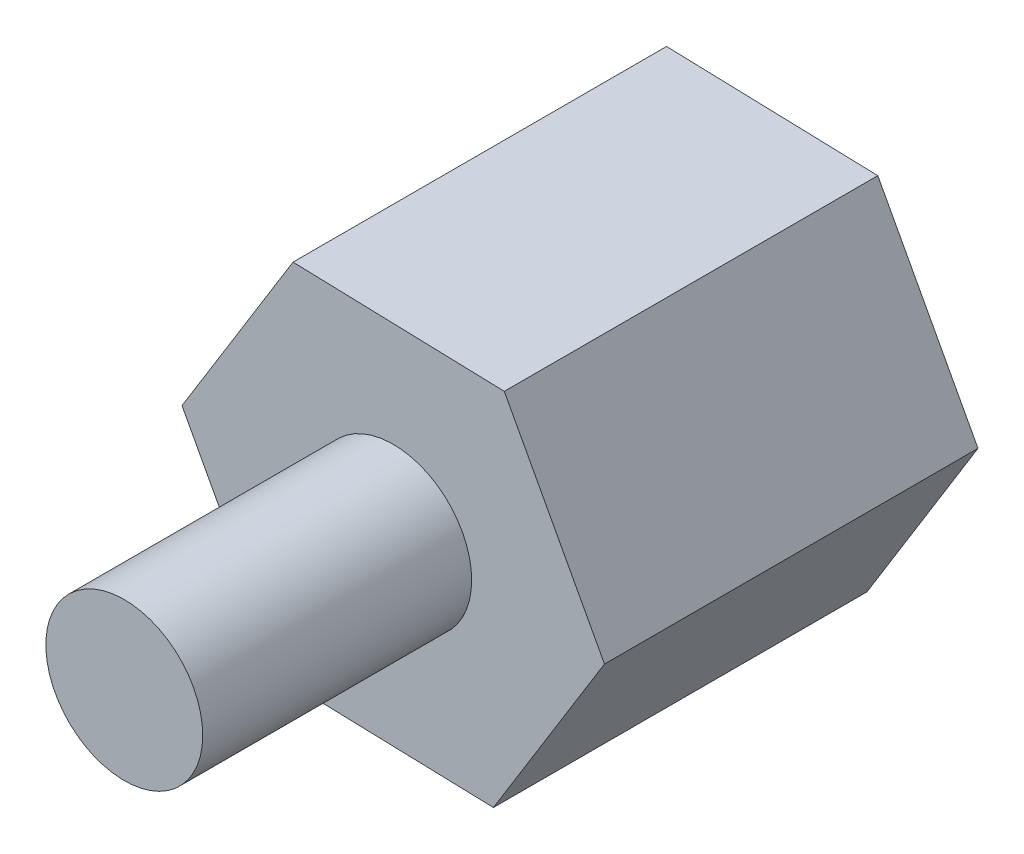
SolidWorks part; units mm, degrees
material "Alloy Steel"
ref_plane "Front Plane" through (0, 0, 0) normal (0, 0, 1) x (1, 0, 0)
ref_plane "Top Plane" through (0, 0, 0) normal (0, 1, 0) x (1, 0, 0)
ref_plane "Right Plane" through (0, 0, 0) normal (1, 0, 0) x (0, 0, -1)
sketch "Sketch1" plane through (0, 0, 0) normal (0, 0, 1) x (1, 0, 0)
  line L1 (1.888, 3.0568) -> (-1.7032, 3.1635)
  line L2 (-1.7032, 3.1635) -> (-3.5913, 0.1067)
  line L3 (-3.5913, 0.1067) -> (-1.888, -3.0568)
  line L4 (-1.888, -3.0568) -> (1.7032, -3.1635)
  line L5 (1.7032, -3.1635) -> (3.5913, -0.1067)
  line L6 (3.5913, -0.1067) -> (1.888, 3.0568)
  circle A0 centre (0, 0) radius 3.1115 construction
  dimension "D1" = 6.223
extrude "Extrude1" add sketch "Sketch1" along normal blind 6.35
sketch "Sketch2" plane through (0, 0, 6.35) normal (0, 0, 1) x (1, 0, 0)
  circle A0 centre (0, 0) radius 1.3335
  dimension "D1" = 2.667
extrude "Extrude2" add sketch "Sketch2" along normal blind 4.572
sketch "Sketch3" plane through (0, 0, 0) normal (0, 0, -1) x (-1, 0, 0)
  circle A0 centre (0, 0) radius 1.3335
  dimension "D1" = 2.667
extrude "Extrude3" cut sketch "Sketch3" against normal blind 5.08
